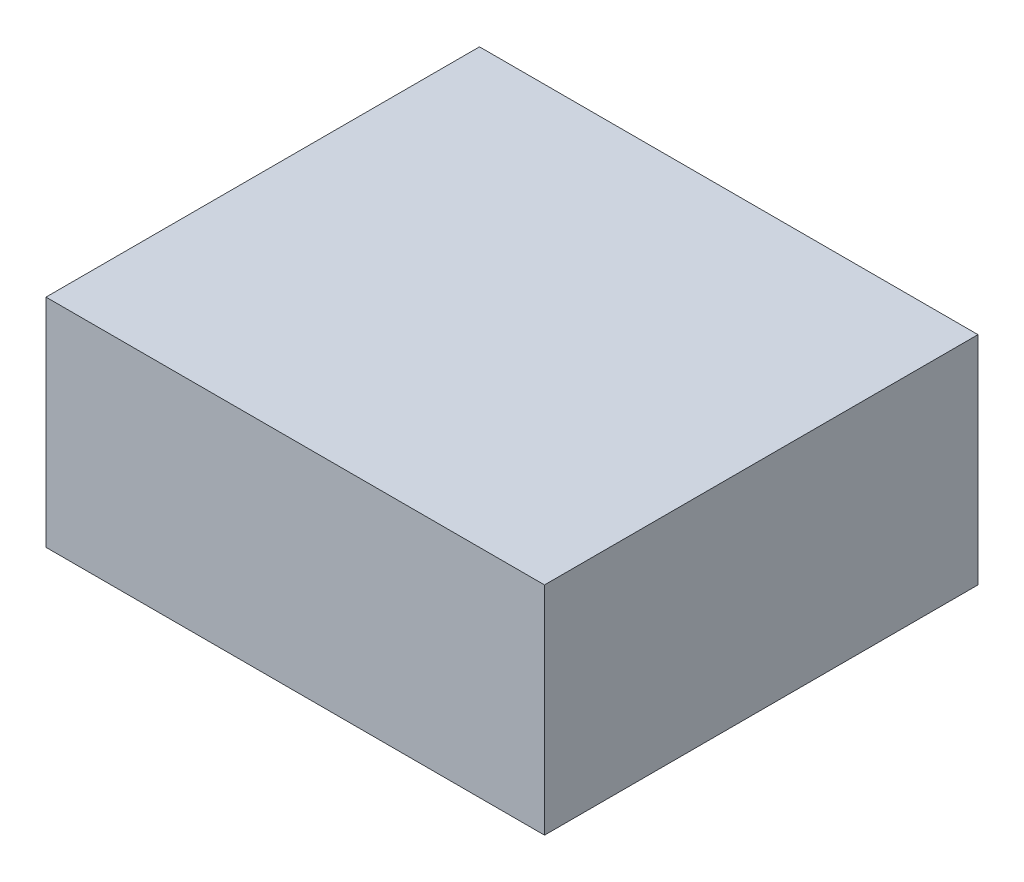
SolidWorks part; units mm, degrees
ref_plane "Front Plane" through (0, 0, 0) normal (0, 0, 1) x (1, 0, 0)
ref_plane "Top Plane" through (0, 0, 0) normal (0, 1, 0) x (1, 0, 0)
ref_plane "Right Plane" through (0, 0, 0) normal (1, 0, 0) x (0, 0, -1)
sketch "Sketch1" plane through (0, 0, 0) normal (0, 1, 0) x (1, 0, 0)
  line L1 (0, 0) -> (23, 0)
  line L2 (0, 0) -> (0, 20)
  line L3 (0, 20) -> (23, 20)
  line L4 (23, 0) -> (23, 20)
extrude "Boss-Extrude1" add sketch "Sketch1" against normal blind 10
